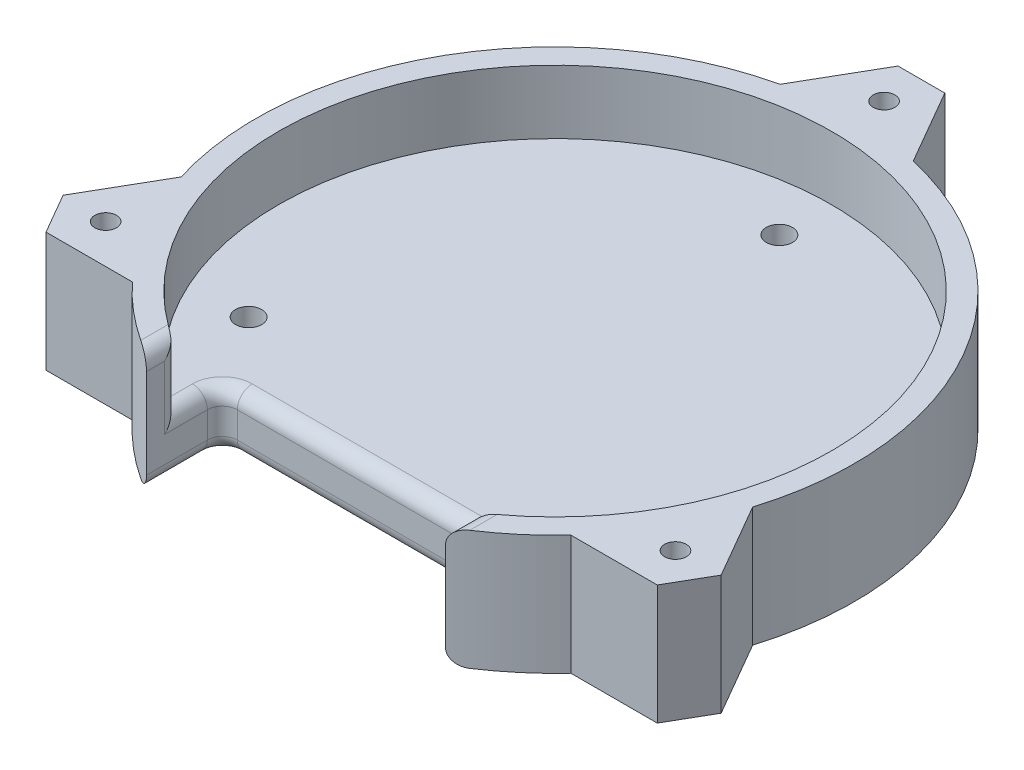
SolidWorks part; units mm, degrees
material "自定义塑料"
ref_plane "前视基准面" through (0, 0, 0) normal (0, 0, 1) x (1, 0, 0)
ref_plane "上视基准面" through (0, 0, 0) normal (0, 1, 0) x (1, 0, 0)
ref_plane "右视基准面" through (0, 0, 0) normal (1, 0, 0) x (0, 0, -1)
other "Configuration Table"
sketch "草图1" plane through (0, 0, 0) normal (0, 1, 0) x (1, 0, 0)
  circle A0 centre (0, 0) radius 40
  dimension "D1" = 80
extrude "凸台-拉伸1" add sketch "草图1" along normal blind 16
sketch "草图2" plane through (0, 16, 0) normal (0, 1, 0) x (1, 0, 0)
  circle A0 centre (0, 0) radius 37
  dimension "D1" = 74
extrude "切除-拉伸1" cut sketch "草图2" against normal blind 8.5
sketch "草图3" plane through (0, 0, 0) normal (0, -1, 0) x (1, 0, 0)
  line L0 (-20, 27.4955) -> (20, 27.4955)
  line L1 (-20, 27.4955) -> (-20, 42.3527)
  line L2 (-20, 42.3527) -> (20, 42.3527)
  line L3 (20, 42.3527) -> (20, 27.4955)
  circle A0 centre (0, 0) radius 34 construction
  dimension "D1" = 68
  dimension "D2" = 40
extrude "切除-拉伸2" cut sketch "草图3" against normal through all
sketch "草图4" plane through (0, 0, 0) normal (0, -1, 0) x (1, 0, 0)
  line L1 (-20, 27.4955) -> (20, 27.4955)
  line L2 (-20, 27.4955) -> (-20, 24.4955)
  line L3 (-20, 24.4955) -> (20, 24.4955)
  line L4 (20, 27.4955) -> (20, 24.4955)
  dimension "D1" = 3
extrude "切除-拉伸3" cut sketch "草图4" against normal through all
sketch "草图5" plane through (0, 0, 0) normal (0, -1, 0) x (1, 0, 0)
  circle A0 centre (0, -30) radius 1.75
  circle A1 centre (-25.9808, 15) radius 1.75
  circle A2 centre (25.9808, 15) radius 1.75
  point P10 (0, 0)
  dimension "D1" = 3.5
  dimension "D2" = 30
  dimension "D3" = 3
extrude "切除-拉伸4" cut sketch "草图5" against normal through all
sketch "草图6" plane through (0, 0, 0) normal (0, -1, 0) x (1, 0, 0)
  line L0 (0, 0) -> (38.1308, 22.0148) construction
  line L1 (29.3271, 27.2098) -> (38.2229, 11.7902)
  line L2 (29.3271, 27.2098) -> (38.2229, 11.7902)
  line L5 (40.8741, 27.2061) -> (43.9997, 21.7883)
  line L6 (8.9009, -39.0029) -> (-8.9009, -38.9971)
  line L8 (27.0981, 15.648) -> (27.0993, 15.6458)
  line L10 (38.2229, 11.7902) -> (43.9997, 21.7883)
  line L12 (40.8741, 27.2061) -> (29.3271, 27.2098)
  line L13 (42.6759, 19.4971) -> (40.4519, 23.352) [skipped]
  line L14 (27.1006, 23.3564) -> (24.8741, 19.5029) [skipped]
  line L15 (33.7725, 11.7916) -> (38.2229, 11.7902) [skipped]
  line L16 (8.9009, -39.0029) -> (-8.9009, -38.9971)
  line L17 (3.1241, -49.001) -> (-3.1306, -48.999)
  line L18 (0.0025, -31.2916) -> (0, -31.2916)
  line L19 (-8.9009, -38.9971) -> (-3.1306, -48.999)
  line L20 (3.1241, -49.001) -> (8.9009, -39.0029)
  line L21 (-38.2279, 11.7931) -> (-29.322, 27.2069)
  line L22 (-38.2279, 11.7931) -> (-29.322, 27.2069)
  line L23 (-43.9982, 21.7949) -> (-40.8691, 27.2107)
  line L24 (-27.1006, 15.6436) -> (-27.0993, 15.6458)
  line L25 (-29.322, 27.2069) -> (-40.8691, 27.2107)
  line L26 (-43.9982, 21.7949) -> (-38.2279, 11.7931)
  arc A0 (-20, 34.641) -> (20, 34.641) centre (0, 0) ccw construction
  arc A3 (27.0981, 15.648) -> (27.0993, 15.6458) centre (33.775, 19.5) ccw construction
  arc A4 (4.1553, -45.4925) -> (6.6744, -42.8564) centre (0, -39) ccw construction
  arc A5 (-6.6769, -42.852) -> (-4.1595, -45.4898) centre (0, -39) ccw construction
  arc A6 (0.0025, -31.2916) -> (0, -31.2916) centre (0, -39) ccw construction
  arc A7 (-41.4753, 19.1477) -> (-40.4519, 15.648) centre (-33.775, 19.5) ccw construction
  arc A8 (-33.7725, 27.2084) -> (-37.3156, 26.3471) centre (-33.775, 19.5) ccw construction
  arc A9 (-27.1006, 15.6436) -> (-27.0993, 15.6458) centre (-33.775, 19.5) ccw construction
  point P3 (34.5834, 19.9667)
  point P4 (33.775, 19.5)
  point P11 (33.775, 19.5)
  point P23 (0, -39.9335)
  point P27 (0, -39)
  point P33 (0, -39)
  point P42 (-34.5834, 19.9667)
  point P43 (-33.775, 19.5)
  point P47 (-33.775, 19.5)
  point P56 (0, 0)
  arc M9 (-20, 34.641) -> (20, 34.641) centre (0, 0) ccw
  dimension "D1" = 39
  dimension "D2" = 3
  dimension "D3" = 17.8018
  dimension "D4" = 10
  dimension "D5" = 6.2548
extrude "凸台-拉伸2" add sketch "草图6" against normal up to surface (16 mm away) contours L5 L12 L1 L10 M9 | L23 L26 L21 L25 M9 | L17 L20 L6 L19 M9 up to face at (0, 16, -2.8076)
sketch "草图10" plane through (0, 16, 0) normal (0, 1, 0) x (1, 0, 0)
  circle A0 centre (0.0001, 44) radius 1.45
  circle A1 centre (38.1051, -22.0001) radius 1.45
  circle A2 centre (-38.1052, -21.9999) radius 1.45
  point P11 (0, 0)
  dimension "D1" = 2.9
  dimension "D3" = 3
extrude "切除-拉伸5" cut sketch "草图10" against normal through all
sketch "草图11" plane through (0, 0, 0) normal (0, -1, 0) x (1, 0, 0)
  line L0 (-39.6929, 19.2499) -> (-36.5175, 19.2499)
  line L1 (3.1755, -44) -> (1.5878, -41.25)
  line L2 (1.5878, -41.25) -> (-1.5876, -41.25)
  line L3 (-1.5876, -41.25) -> (-3.1753, -44)
  line L4 (-3.1753, -44) -> (-1.5876, -46.75)
  line L5 (-1.5876, -46.75) -> (1.5878, -46.75)
  line L6 (1.5878, -46.75) -> (3.1755, -44)
  line L7 (-36.5175, 19.2499) -> (-34.9297, 21.9999)
  line L8 (-34.9297, 21.9999) -> (-36.5175, 24.7499)
  line L9 (-36.5175, 24.7499) -> (-39.6929, 24.7499)
  line L10 (-39.6929, 24.7499) -> (-41.2806, 21.9999)
  line L11 (-41.2806, 21.9999) -> (-39.6929, 19.2499)
  line L12 (36.5173, 24.7501) -> (34.9296, 22.0001)
  line L13 (34.9296, 22.0001) -> (36.5173, 19.2501)
  line L14 (36.5173, 19.2501) -> (39.6928, 19.2501)
  line L15 (39.6928, 19.2501) -> (41.2805, 22.0001)
  line L16 (41.2805, 22.0001) -> (39.6928, 24.7501)
  line L17 (39.6928, 24.7501) -> (36.5173, 24.7501)
  circle A0 centre (0.0001, -44) radius 2.75 construction
  circle A1 centre (-38.1052, 21.9999) radius 2.75 construction
  circle A2 centre (38.1051, 22.0001) radius 2.75 construction
  point P28 (0, 0)
  dimension "D1" = 5.5
  dimension "D2" = 3
extrude "切除-拉伸6" cut sketch "草图11" against normal blind 2.6
sketch "草图13" plane through (0, 0, 0) normal (0, -1, 0) x (1, 0, 0)
  circle A0 centre (-25.9808, 15) radius 3.5
  circle A1 centre (25.9808, 15) radius 3.5
  circle A2 centre (0, -30) radius 3.5
  point P10 (0, 0)
  dimension "D1" = 7
  dimension "D2" = 3
extrude "切除-拉伸7" cut sketch "草图13" against normal blind 4 contours A0 | A2 | A1
fillet "圆角2" radius 2 8 edges at (-20, 0, 29.5682) (20, 0, 29.5682) (0, 7.5, 24.4955) (0, 0, 24.4955) (-20, 7.5, 27.8121) (-20, 3.75, 24.4955) (20, 3.75, 24.4955) (20, 7.5, 27.8121)
fillet "圆角3" radius 2 4 edges at (-20, 16, 32.8849) (-20, 10.75, 31.1288) (20, 10.75, 31.1288) (20, 16, 32.8849)
